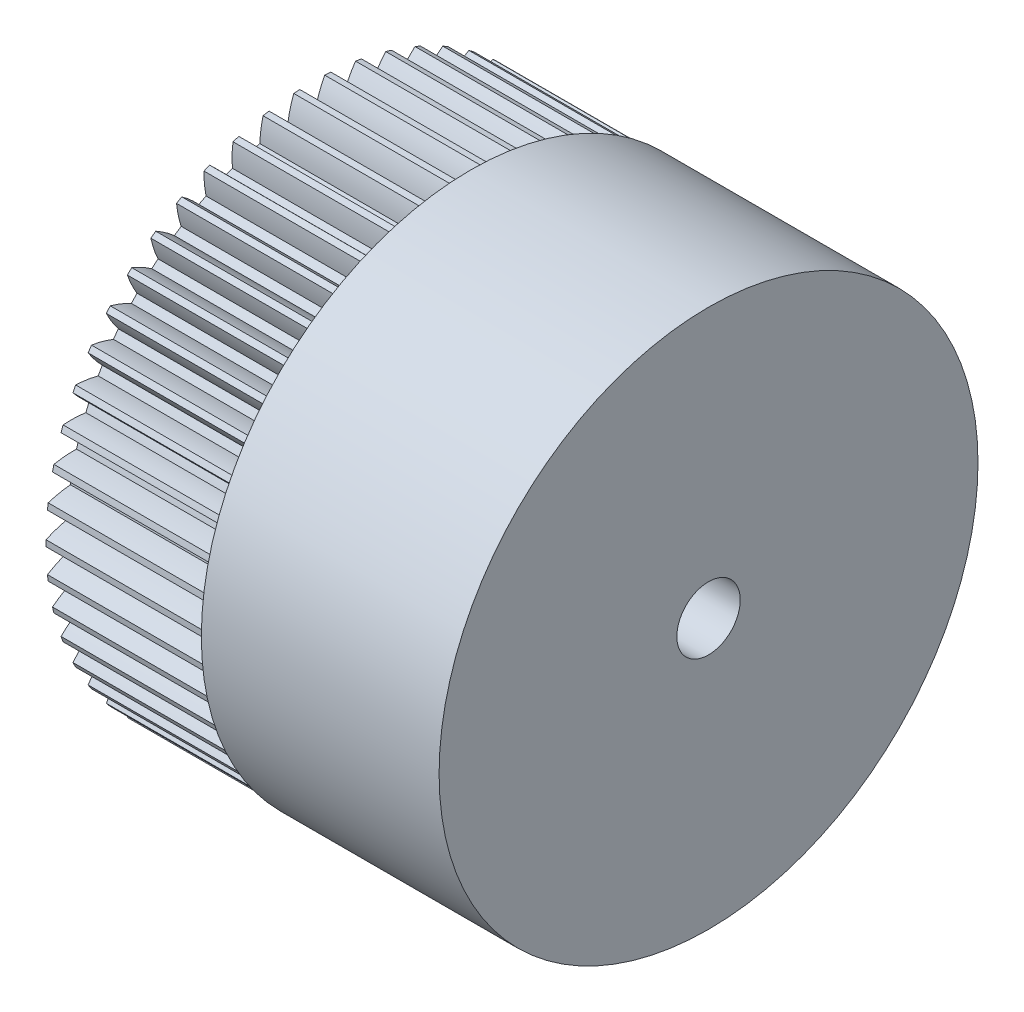
SolidWorks part; units mm, degrees
ref_plane "Plane1" through (0, 0, 0) normal (0, 0, 1) x (1, 0, 0)
ref_plane "Plane2" through (0, 0, 0) normal (0, 1, 0) x (1, 0, 0)
ref_plane "Plane3" through (0, 0, 0) normal (1, 0, 0) x (0, 0, -1)
other "Configuration Table"
sketch "HoldingSke" plane through (0, 0, 0) normal (0, 1, 0) x (1, 0, 0)
  line L0 (0, 0) -> (0.9796, -1.3484)
  line L1 (-15, 0) -> (100, 0) construction
  line L2 (0, 0) -> (-2.1039, 2.3779)
  line L3 (0, 0) -> (-11.863, 4.5341)
  line L4 (0, 0) -> (5.0761, 6.9867)
  line L5 (0, 0) -> (-46.8476, -17.4728)
  line L6 (0, 0) -> (-4.1448, -2.7965)
  line L7 (-2.1039, 2.3779) -> (8.6588, 51.2067)
  line L8 (-76.2, 54.61) -> (-75.7, 54.61)
  line L9 (-71.009, 38.7566) -> (-53.1078, 45.2721)
  line L10 (-76.2, 71.12) -> (104.1128, 71.12)
  line L11 (0, 0) -> (-5, 0)
  line L12 (-76.2, 101.6) -> (-76.177, 101.6)
  line L13 (24.9733, 27.94) -> (52.9518, 28.4284)
  line L14 (24.9733, 27.94) -> (24.9743, 27.94)
  line L15 (24.9733, 27.94) -> (100.4006, 29.5858)
  line L16 (-63.627, -0.6) -> (-12.827, -0.6)
  circle A0 centre (0, 0) radius 1.5
  circle A1 centre (0, 0) radius 15.449
  circle A2 centre (0, 0) radius 37.5
  circle A3 centre (0, 0) radius 1.5
  dimension "MHD" = 30.898
  dimension "Hub_dia" = 75
  dimension "Bore" = 3
  dimension "MBD" = 3
  dimension "Num_teeth" = 54
  dimension "Pitch" = 1.6667
  dimension "Overall_len" = 50
  dimension "Show_teeth" = 54
  dimension "Thickness" = 5
  dimension "OAL" = 50.0009
  dimension "T_dim" = 0.5
  dimension "Ap" = 20
  dimension "H" = 19.05
  dimension "Pitch_radius" = 180.3128
  dimension "Width" = 5
  dimension "Backlash" = 0.023
  dimension "Addendum_fac" = 1
  dimension "Dedendum_fac" = 1.25
  dimension "Clearance_fac" = 0.25
  dimension "Dedendum_add" = 0.001
  dimension "Module" = 0.6
sketch "BasProSke" plane through (0, 0, 0) normal (0, 1, 0) x (1, 0, 0)
  line L0 (-10, 0) -> (60, 0) construction
  line L1 (0, 0) -> (0, 16.8)
  line L2 (0, 0) -> (10, 0)
  line L3 (10, 0) -> (10, 16.8)
  line L4 (10, 16.8) -> (0, 16.8)
  dimension "Thickness" = 10
  dimension "Diameter" = 33.6
revolve "Base-Revolve" add sketch "BasProSke" angle 360 about L0
sketch "TooCutSke" plane through (0, 0, 0) normal (1, 0, 0) x (0, 0, -1)
  line L1 (0, 0) -> (0, 107) construction
  line L2 (0, 0) -> (-0.5114, 16.1919) construction
  line L3 (0, 0) -> (-1.8832, 32.3337) construction
  line L4 (-0.5114, 16.1919) -> (-0.9416, 16.1669) construction
  arc A0 (0.2608, 15.4468) -> (-0.2608, 15.4468) centre (0, 0) ccw
  arc A1 (0.7988, 16.8064) -> (-0.7988, 16.8064) centre (0, 0) ccw
  circle A2 centre (0, 0) radius 16.2 construction
  circle A3 centre (0, 0) radius 15.223 construction
  arc A4 (-0.2608, 15.4468) -> (-0.7988, 16.8064) centre (-6.5168, 13.7576) ccw
  arc A5 (0.7988, 16.8064) -> (0.2608, 15.4468) centre (6.5168, 13.7576) ccw
  dimension "Root_dia" = 30.898
  dimension "Overcut_dia" = 33.6508
  dimension "Pitch_dia" = 32.4
  dimension "Base_dia" = 30.446
  dimension "Flank_rad" = 6.48
  dimension "Half_ang" = 3.333
  dimension "Half_CT" = 0.4309
extrude "ToothCut" cut sketch "TooCutSke" along normal through all
fillet "Breaks" [suppressed] radius 0.012
fillet "RootFillets" [suppressed] radius 0.151
pattern_circular "TeethCuts" count 54 every 6.667 about axis through (-10, 0, 0) along (1, 0, 0) of "ToothCut", "RootFillets", "Breaks"
sketch "HubNeaOneSke" plane through (0, 0, 0) normal (-1, 0, 0) x (0, 0, 1)
  circle A0 centre (0, 0) radius 15.449
  dimension "Diameter" = 30.898
extrude "HubNearOne" [suppressed] add sketch "HubNeaOneSke" along normal blind 40.0009
sketch "HubNeaBotSke" plane through (0, 0, 0) normal (-1, 0, 0) x (0, 0, 1)
  circle A0 centre (0, 0) radius 15.449
  dimension "Diameter" = 30.898
extrude "HubNearBoth" [suppressed] add sketch "HubNeaBotSke" along normal blind 20.0004
ref_plane "FarPln" through (10, 0, 0) normal (1, 0, 0) x (0, 0, -1)
sketch "HubFarSke" plane through (10, 0, 0) normal (1, 0, 0) x (0, 0, -1)
  circle A0 centre (0, 0) radius 15.449
  dimension "Diameter" = 30.898
extrude "HubFar" [suppressed] add sketch "HubFarSke" along normal blind 20.0004
sketch "BorSke" plane through (0, 0, 0) normal (1, 0, 0) x (0, 0, -1)
  circle A0 centre (0, 0) radius 2
  dimension "Diameter" = 4
extrude "Bore" cut sketch "BorSke" along normal mid plane 100.0017
sketch "KeySke" plane through (0, 0, 0) normal (1, 0, 0) x (0, 0, -1)
  line L0 (-0.6, 0) -> (-0.6, 2)
  line L1 (-0.6, 2) -> (0.6, 2)
  line L2 (0.6, 2) -> (0.6, 0)
  line L3 (0, 0) -> (0, 34) construction
  line L4 (-0.6, 0) -> (0.6, 0)
  dimension "Offset" = 2
  dimension "Width" = 1.2
extrude "Keyway" [suppressed] cut sketch "KeySke" along normal mid plane 100.0017
pattern_circular "Keyway2" [suppressed] count 2 every 90 about axis through (-10, 0, 0) along (1, 0, 0)
sketch "Sketch1" plane through (10, 0, 0) normal (1, 0, 0) x (0, 0, -1)
  circle A0 centre (0, 0) radius 17
  circle A1 centre (0, 0) radius 2
  dimension "D1" = 34
  dimension "D2" = 4
extrude "Boss-Extrude1" add sketch "Sketch1" along normal blind 15
equation "' \"Module@HoldingSke\" = 6.35"
equation "' \"Num_teeth@HoldingSke\" = 12"
equation "' \"Ap@HoldingSke\" =  20"
equation "' \"Ap@HoldingSke\" = 20"
equation "'\"Width@HoldingSke\" = 0.5 * 25.4"
equation "' \"Hub_dia@HoldingSke\"= 1 * 25.4"
equation "' \"Hub_dia@HoldingSke\" = 1 * 25.4"
equation "' \"Overall_len@HoldingSke\" = 1.0 * 25.4"
equation "' \"Bore@HoldingSke\" = 0.75 * 25.4"
equation "' \"T_dim@HoldingSke\" = 0.1 * 25.4"
equation "' \"Width@KeySke\" = 0.25 * 25.4"
equation "' \"Show_teeth@HoldingSke\" = 13"
equation "' \"Backlash@HoldingSke\" = 0.009 * 25.4"
equation "' \"Addendum_fac@HoldingSke\" = 1.0"
equation "' \"Dedendum_fac@HoldingSke\" = 1.25"
equation "' \"Dedendum_add@HoldingSke\" = 0.00005 * 25.4"
equation "' \"Clearance_fac@HoldingSke\" = 0.25"
equation "\"Pitch@HoldingSke\" = 1 / \"Module@HoldingSke\""
equation "\"Overcut_dia@TooCutSke\" = (\"Num_teeth@HoldingSke\" + 2 * \"Addendum_fac@HoldingSke\") / \"Pitch@HoldingSke\" + 0.002 * 25.4"
equation "\"Pitch_dia@TooCutSke\" = \"Num_teeth@HoldingSke\" / \"Pitch@HoldingSke\""
equation "\"Base_dia@TooCutSke\" = \"Num_teeth@HoldingSke\" / \"Pitch@HoldingSke\" * cos((\"Ap@HoldingSke\"  * 3.14159265 / 180))"
equation "\"Root_dia@TooCutSke\" = (\"Num_teeth@HoldingSke\" + 2) / \"Pitch@HoldingSke\" - 2 * (\"Addendum_fac@HoldingSke\" + \"Dedendum_fac@HoldingSke\") / \"Pitch@HoldingSke\" - \"Dedendum_add@HoldingSke\" * 2"
equation "\"Half_ang@TooCutSke\" = 180 / \"Num_teeth@HoldingSke\""
equation "\"Half_CT@TooCutSke\" = \"Num_teeth@HoldingSke\" / \"Pitch@HoldingSke\" * sin((3.14159265 / 2 / \"Num_teeth@HoldingSke\")) / 2 - 7 * \"Backlash@HoldingSke\" / 4"
equation "\"Flank_rad@TooCutSke\" = \"Num_teeth@HoldingSke\" / \"Pitch@HoldingSke\" / 5"
equation "\"Radius@RootFillets\" = \"Clearance_fac@HoldingSke\" / \"Pitch@HoldingSke\" + \"Dedendum_add@HoldingSke\""
equation "\"Break_rad@Breaks\" = 0.02 / \"Pitch@HoldingSke\""
equation "\"Thickness@HoldingSke\"= \"Width@HoldingSke\""
equation "\"OAL@HoldingSke\" = \"Thickness@HoldingSke\""
equation "\"MHD@HoldingSke\" = (\"Num_teeth@HoldingSke\" + 2) / \"Pitch@HoldingSke\" - 2 * (\"Addendum_fac@HoldingSke\" + \"Dedendum_fac@HoldingSke\")  / \"Pitch@HoldingSke\" - \"Dedendum_add@HoldingSke\" * 2"
equation "\"MBD@HoldingSke\" = (\"Num_teeth@HoldingSke\" + 2) / \"Pitch@HoldingSke\" - 2 * (\"Addendum_fac@HoldingSke\" + \"Dedendum_fac@HoldingSke\")  / \"Pitch@HoldingSke\" - \"Dedendum_add@HoldingSke\" * 2 - 0.002 * 25.4"
equation "\"MHD@HoldingSke\" = ((sgn( \"MHD@HoldingSke\" - \"Hub_dia@HoldingSke\" )-1)*( \"MHD@HoldingSke\" - \"Hub_dia@HoldingSke\" ))/-2+ \"Hub_dia@HoldingSke\""
equation "\"MBD@HoldingSke\" = ((sgn( \"MBD@HoldingSke\" - \"Bore@HoldingSke\" )-1)*( \"MBD@HoldingSke\" - \"Bore@HoldingSke\" ))/-2+ \"Bore@HoldingSke\""
equation "\"OAL@HoldingSke\" = ((sgn( \"OAL@HoldingSke\" - \"Overall_len@HoldingSke\" )+1)*( \"OAL@HoldingSke\" - \"Overall_len@HoldingSke\" ))/2 + \"Overall_len@HoldingSke\" + 0.000002 * 25.4"
equation "\"Num_teeth@TeethCuts\" = int( \"Show_teeth@HoldingSke\" ) + 1"
equation "\"Num_teeth@TeethCuts\" = ((sgn( \"Num_teeth@TeethCuts\" - \"Num_teeth@HoldingSke\" )-1)*( \"Num_teeth@TeethCuts\" - \"Num_teeth@HoldingSke\" ))/-2+ \"Num_teeth@HoldingSke\""
equation "\"Num_teeth@TeethCuts\" = ((sgn( \"Num_teeth@TeethCuts\" - 2.0)+1)*( \"Num_teeth@TeethCuts\" - 2.0))/2 +2.0"
equation "\"Angle@TeethCuts\" = 360.0 / \"Num_teeth@HoldingSke\""
equation "\"Diameter@BasProSke\" = (\"Num_teeth@HoldingSke\" + 2 * \"Addendum_fac@HoldingSke\") / \"Pitch@HoldingSke\""
equation "' \"Fillet_rad@BasProSke\" =  \"Thickness@HoldingSke\" * 0.05"
equation "' \"Fillet_rad@BasProSke\" = \"Thickness@HoldingSke\" * 0.05"
equation "\"MHD@HoldingSke\" = ((sgn( \"MHD@HoldingSke\" - \"Root_dia@TooCutSke\" )-1)*( \"MHD@HoldingSke\" - \"Root_dia@TooCutSke\" ))/-2+ \"Root_dia@TooCutSke\""
equation "\"Diameter@HubNeaOneSke\" = \"MHD@HoldingSke\""
equation "\"Length@HubNearOne\" = \"OAL@HoldingSke\" - \"Thickness@BasProSke\""
equation "\"Diameter@HubNeaBotSke\" = \"MHD@HoldingSke\""
equation "\"Length@HubNearBoth\" = ( \"OAL@HoldingSke\" - \"Thickness@BasProSke\" ) / 2.0"
equation "\"Thickness@FarPln\" = \"Thickness@BasProSke\""
equation "\"Diameter@HubFarSke\" = \"MHD@HoldingSke\""
equation "\"Length@HubFar\" = ( \"OAL@HoldingSke\" - \"Thickness@BasProSke\" ) / 2.0"
equation "\"D1@Bore\" = \"OAL@HoldingSke\" * 2.0"
equation "\"D1@Keyway\" = \"OAL@HoldingSke\" * 2.0"
equation "\"Offset@KeySke\" = \"T_dim@HoldingSke\" + \"MBD@HoldingSke\" / 2.0"
